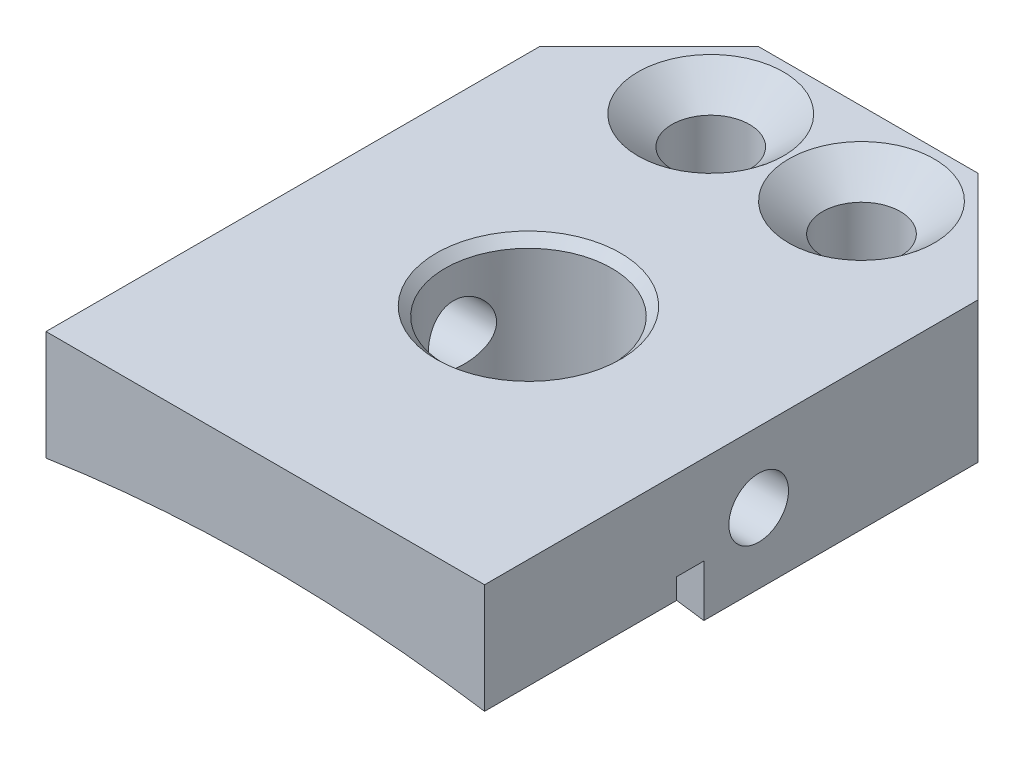
SolidWorks part; units mm, degrees
ref_plane "Front Plane" through (0, 0, 0) normal (0, 0, 1) x (1, 0, 0)
ref_plane "Top Plane" through (0, 0, 0) normal (0, 1, 0) x (1, 0, 0)
ref_plane "Right Plane" through (0, 0, 0) normal (1, 0, 0) x (0, 0, -1)
sketch "Sketch1" plane through (0, 0, 0) normal (0, 1, 0) x (1, 0, 0)
  line L0 (-28.5118, 16.0203) -> (-22.1618, 22.3703)
  line L1 (-22.1618, 22.3703) -> (-9.4618, 22.3703)
  line L2 (-28.5118, 16.0203) -> (-28.5118, -12.5547)
  line L3 (-28.5118, -12.5547) -> (-3.1118, -12.5547)
  line L4 (-3.1118, 16.0203) -> (-3.1118, -12.5547)
  line L5 (-9.4618, 22.3703) -> (-3.1118, 16.0203)
  line L6 (-15.8118, -12.5547) -> (-15.8118, 22.3703) construction
  line L8 (-3.1118, 16.0203) -> (-3.1118, 22.3703) construction
  line L9 (-3.1118, 22.3703) -> (-9.4618, 22.3703) construction
  dimension "D1" = 12.7
  dimension "D2" = 34.925
  dimension "D3" = 25.4
extrude "Boss-Extrude1" add sketch "Sketch1" along normal blind 6.35
sketch "Sketch2" plane through (0, 0, 12.5547) normal (0, 0, 1) x (1, 0, 0)
  circle A0 centre (-15.8118, -82.8523) radius 83.82
  dimension "D1" = 167.64
extrude "Cut-Extrude1" cut sketch "Sketch2" against normal through all both and the other way through all
sketch "Sketch5" plane through (0, 0, -22.3703) normal (0, 0, -1) x (-1, 0, 0)
  line L0 (3.1118, 6.35) -> (3.1118, 0) construction
  line L1 (3.1118, 6.35) -> (3.1118, 0)
  line L4 (28.5118, 6.35) -> (28.5118, 0) construction
  line L5 (28.5118, 6.35) -> (28.5118, 0)
  line L6 (28.5118, -1.7992) -> (28.5118, 0)
  line L7 (3.1118, -1.7992) -> (3.1118, 0)
  line L8 (3.1118, 6.35) -> (28.5118, 6.35)
  arc A0 (3.1118, -1.7992) -> (28.5118, -1.7992) centre (15.8118, -82.8523) cw
  arc A1 (28.5118, 0) -> (3.1118, 0) centre (15.8118, -82.8523) ccw construction
  arc A2 (28.5118, 0) -> (3.1118, 0) centre (15.8118, -82.8523) ccw construction
  dimension "D1" = 82.042
extrude "Boss-Extrude2" add sketch "Sketch5" against normal blind 22.225
chamfer "Chamfer1" distance 6.35 angle 45 2 edges at (-28.5118, 2.2754, -22.3703) (-3.1118, 2.2754, -22.3703)
hole_wizard "CSK for #8 Flat Head Machine Screw (100)1" positions "Sketch3" profile "Sketch4" countersink size "#8" standard "ANSI Inch" end condition through all
sketch "Sketch3" plane through (0, 6.35, 0) normal (0, 1, 0) x (1, 0, 0)
  line L0 (-15.8118, 22.3703) -> (-15.8118, 3.4006) construction
  line L1 (-9.4618, 22.3703) -> (-22.1618, 22.3703) construction
  point P0 (-20.1775, 17.6078)
  point P12 (-11.4462, 17.6078)
  dimension "D1" = 4.7625
  dimension "D2" = 4.3656
sketch "Sketch4" plane through (-20.1775, 6.35, -17.6078) normal (1, 0, 0) x (0, 0, 1)
  line L0 (0, 0) -> (0, 8.1492)
  line L1 (0, 8.1492) -> (2.2479, 8.1492)
  line L2 (2.2479, 8.1492) -> (2.2479, 1.6518)
  line L3 (2.2479, 1.6518) -> (4.2164, 0)
  line L5 (4.2164, 0) -> (0, 0)
  line L6 (-2.2479, 1.6518) -> (-4.2164, 0) construction
  line L11 (0, -6.35) -> (0, 107.95) construction
  dimension "Thru Hole Dia." = 4.4958
  dimension "Thru Hole Depth" = 8.1492
  dimension "Near C'Sink Dia." = 8.4328
  dimension "Near C'Sink Angle" = 100
sketch "Sketch6" plane through (0, 6.35, 0) normal (0, 1, 0) x (1, 0, 0)
  line L0 (-9.4618, 22.3703) -> (-22.1618, 22.3703) construction
  line L1 (-15.8118, -12.5547) -> (-15.8118, 22.3703) construction
  line L2 (-28.5118, -12.5547) -> (-3.1118, -12.5547) construction
  circle A1 centre (-15.8118, 2.6853) radius 1.524
  dimension "D1" = 3.048
  dimension "D2" = 19.685
extrude "Cut-Extrude2" cut sketch "Sketch6" against normal through all
sketch "Sketch7" plane through (-3.1118, 0, 0) normal (1, 0, 0) x (0, 0, -1)
  line L1 (0.1453, -1.7992) -> (-1.4422, -1.7992)
  line L2 (0.1453, -1.7992) -> (0.1453, 1.1906)
  line L3 (0.1453, 1.1906) -> (-1.4422, 1.1906)
  line L4 (-1.4422, -1.7992) -> (-1.4422, 1.1906)
  line L5 (0.1453, -1.7992) -> (16.0203, -1.7992) construction
  line L6 (-12.5547, 0) -> (0.1453, 0) construction
  line L7 (0.1453, 0) -> (0.1453, -1.7992) construction
  dimension "D1" = 1.5875
  dimension "D2" = 1.1906
extrude "Cut-Extrude3" cut sketch "Sketch7" against normal through all
sketch "Sketch8" plane through (0, 6.35, 0) normal (0, 1, 0) x (1, 0, 0)
  circle A0 centre (-15.8118, 2.6853) radius 4.826
  dimension "D1" = 9.652
extrude "Cut-Extrude4" cut sketch "Sketch8" against normal through all
chamfer "Chamfer2" distance 0.508 angle 45 1 edges at (-15.8118, 6.35, 2.1407)
hole_wizard "#8-32 Tapped Hole1" positions "Sketch9" profile "Sketch10" tap size "#8-32" standard "ANSI Inch" end condition through all
sketch "Sketch9" plane through (-28.5118, 0, 0) normal (-1, 0, 0) x (0, 0, 1)
  line L0 (2.1407, 5.842) -> (-7.5113, 5.842) construction
  line L1 (2.1407, 5.842) -> (-7.5113, 5.842)
  line L2 (-3.3203, 6.35) -> (-3.3203, -1.7992) construction
  line L3 (-16.0203, 6.35) -> (12.5547, 6.35) construction
  line L4 (-0.1453, -1.7992) -> (-16.0203, -1.7992) construction
  point P0 (-3.3203, 2.2754)
  point P13 (-2.6853, 5.842)
  dimension "D1" = 0.635
sketch "Sketch10" plane through (-28.5118, 2.2754, -3.3203) normal (0, 1, 0) x (0, 0, 1)
  line L0 (0, 0) -> (0, 25.4)
  line L1 (0, 25.4) -> (1.7272, 25.4)
  line L2 (1.7272, 25.4) -> (1.7272, 0)
  line L5 (1.7272, 0) -> (0, 0)
  line L11 (0, -6.35) -> (0, 107.95) construction
  dimension "Thru Tap Drill Dia." = 3.4544
  dimension "Thru Tap Drill Depth" = 25.4
cosmetic thread "Hole Thread1" parameters "D2"=4.1656
